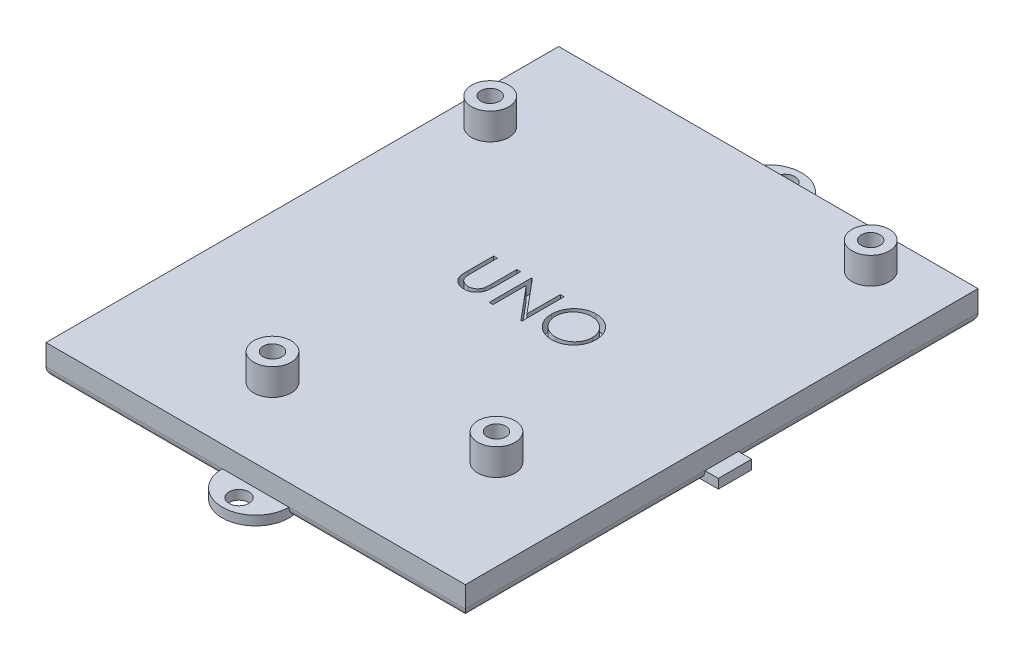
SolidWorks part; units mm, degrees
ref_plane "Front Plane" through (0, 0, 0) normal (0, 0, 1) x (1, 0, 0)
ref_plane "Top Plane" through (0, 0, 0) normal (0, 1, 0) x (1, 0, 0)
ref_plane "Right Plane" through (0, 0, 0) normal (1, 0, 0) x (0, 0, -1)
sketch "Sketch1" plane through (0, 0, 0) normal (0, 1, 0) x (1, 0, 0)
  line L0 (-31.45, 38.45) -> (31.45, 38.45)
  line L5 (-31.45, 38.45) -> (-31.45, -38.45)
  line L6 (-31.45, -38.45) -> (31.45, -38.45)
  line L7 (31.45, 38.45) -> (31.45, -38.45)
  point P11 (-31.45, 0)
  point P12 (0, -38.45)
  dimension "D3" = 76.9
  dimension "D4" = 62.9
extrude "Boss-Extrude1" add sketch "Sketch1" along normal blind 4.575
sketch "Sketch2" plane through (0, 4.575, 0) normal (0, 1, 0) x (1, 0, 0)
  line L0 (17.8977, -20.2309) -> (6.2677, 29.2199) construction
  line L1 (21.1029, 32.709) -> (6.2677, 29.2199) construction
  line L2 (17.8977, -20.2309) -> (-9.3002, -26.6274) construction
  line L3 (-9.3002, -26.6274) -> (-21.221, 24.0597) construction
  line L4 (0, -38.45) -> (0, 38.45) construction
  line L5 (-31.45, 0) -> (31.45, 0) construction
  line L6 (-21.221, 24.0597) -> (-26.1661, 22.8967) construction
  line L11 (-31.45, 38.45) -> (-31.45, -38.45) construction
  line L12 (-31.45, -38.45) -> (31.45, -38.45) construction
  line L13 (31.45, 38.45) -> (-31.45, 38.45) construction
  line L14 (31.45, -38.45) -> (31.45, 38.45) construction
  circle A0 centre (17.8977, -20.2309) radius 2.8
  circle A1 centre (21.1029, 32.709) radius 2.8
  circle A2 centre (-26.1661, 22.8967) radius 2.8
  circle A3 centre (-9.3002, -26.6274) radius 2.8
  circle A4 centre (21.1029, 32.709) radius 1.4
  circle A5 centre (17.8977, -20.2309) radius 1.4
  circle A6 centre (-9.3002, -26.6274) radius 1.4
  circle A7 centre (-26.1661, 22.8967) radius 1.4
  dimension "D7" = 2.8
  dimension "D10" = 1.4
  dimension "D1" = 27.94
  dimension "D2" = 15.24
  dimension "D3" = 5.08
  dimension "D4" = 1.27
  dimension "D5" = 50.8
  dimension "D6" = 13.235
  dimension "D8" = 9.3002
  dimension "D9" = 26.6274
extrude "Boss-Extrude2" add sketch "Sketch2" along normal blind 4
sketch "Sketch3" plane through (0, 4.575, 0) normal (0, 1, 0) x (1, 0, 0)
  circle A0 centre (17.8977, -20.2309) radius 1.4
  circle A1 centre (-9.3002, -26.6274) radius 1.4
  circle A2 centre (-26.1661, 22.8967) radius 1.4
  circle A3 centre (21.1029, 32.709) radius 1.4
  circle A4 centre (21.1029, 32.709) radius 1.4 construction
  circle A5 centre (-26.1661, 22.8967) radius 1.4 construction
extrude "Cut-Extrude1" cut sketch "Sketch3" against normal offset from surface (3.575 mm away) 1 up to face at (0, 0, 0)
sketch "Sketch4" plane through (0, 0, 0) normal (0, 1, 0) x (1, 0, 0)
  line L0 (-5, -38.45) -> (5, -38.45)
  line L2 (-31.45, -38.45) -> (31.45, -38.45) construction
  line L4 (0, -38.45) -> (0, -43.45) construction
  arc A0 (-5, -38.45) -> (5, -38.45) centre (0, -38.45) ccw
  circle A2 centre (0, -40.95) radius 1.5
  dimension "D2" = 3
  dimension "D3" = 5
extrude "Boss-Extrude3" add sketch "Sketch4" along normal blind 1.4
mirror "Mirror1" about plane through (0, 0, 0) normal (0, 0, 1) of "Boss-Extrude3"
sketch "Sketch5" plane through (0, 4.575, 0) normal (0, 1, 0) x (1, 0, 0)
  line L0 (-15, 0) -> (15, 0) construction
  text T0 "UNO" font "Century Gothic" height in points 24
  point P6 (0, 0)
  dimension "D1" = 30
extrude "Cut-Extrude2" cut sketch "Sketch5" against normal blind 2
sketch "Sketch6" plane through (-31.45, 0, 0) normal (-1, 0, 0) x (0, 0, 1)
  line L0 (-38.45, 0) -> (38.45, 0) construction
  line L1 (-2.5, 0) -> (2.5, 0)
  line L2 (-2.5, 0) -> (-2.5, 1.4)
  line L3 (-2.5, 1.4) -> (2.5, 1.4)
  line L4 (2.5, 0) -> (2.5, 1.4)
  line L5 (43.45, 1.4) -> (38.45, 1.4) construction
  point P6 (0, 0)
  point P7 (0, 1.4)
  dimension "D1" = 5
extrude "Boss-Extrude4" add sketch "Sketch6" along normal blind 2
mirror "Mirror2" about plane through (0, 0, 0) normal (1, 0, 0) of "Boss-Extrude4"
fillet "Fillet1" radius 1.4 8 edges at (-18.225, 0, 38.45) (18.225, 0, 38.45) (31.45, 0, -20.475) (31.45, 0, 20.475) (18.225, 0, -38.45) (-18.225, 0, -38.45) (-31.45, 0, 20.475) (-31.45, 0, -20.475)
